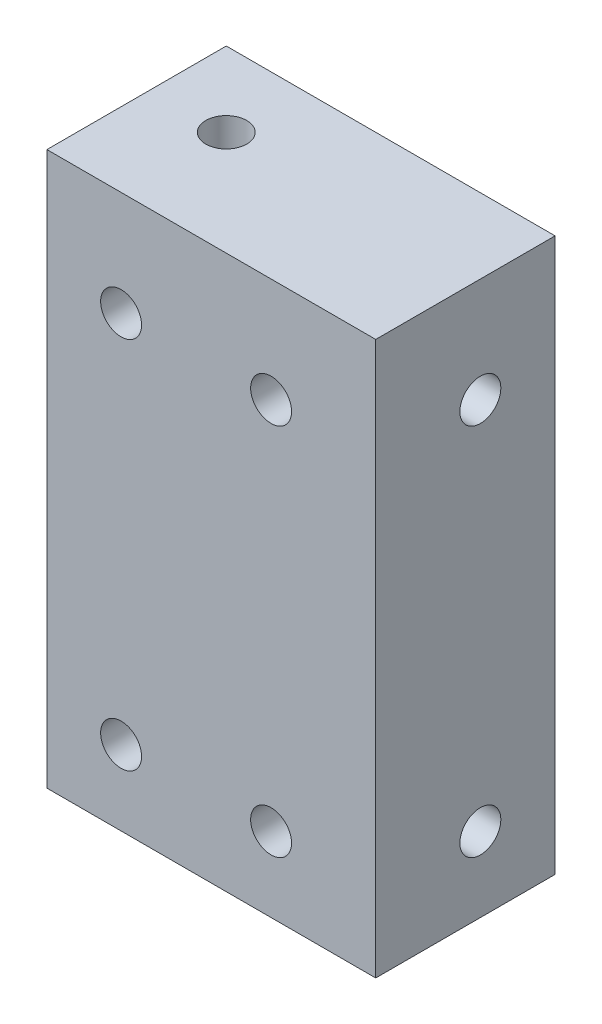
SolidWorks part; units mm, degrees
ref_plane "Front Plane" through (0, 0, 0) normal (0, 0, 1) x (1, 0, 0)
ref_plane "Top Plane" through (0, 0, 0) normal (0, 1, 0) x (1, 0, 0)
ref_plane "Right Plane" through (0, 0, 0) normal (1, 0, 0) x (0, 0, -1)
sketch "Sketch1" plane through (0, 0, 0) normal (0, 0, 1) x (1, 0, 0)
  line L1 (-229.0682, -521.2775) -> (-189.0682, -521.2775)
  line L2 (-229.0682, -521.2775) -> (-229.0682, -451.2775)
  line L3 (-229.0682, -451.2775) -> (-189.0682, -451.2775)
  line L4 (-189.0682, -521.2775) -> (-189.0682, -451.2775)
  line L5 (-229.0682, -521.2775) -> (-189.0682, -451.2775) construction
  line L6 (-229.0682, -451.2775) -> (-189.0682, -521.2775) construction
  circle A0 centre (-199.0682, -461.2775) radius 2.74
  circle A1 centre (-219.1391, -461.2775) radius 2.74
  circle A2 centre (-219.1391, -511.2775) radius 2.74
  circle A3 centre (-199.0682, -511.2775) radius 2.74
  point P0 (-209.0682, -486.2775)
  point P13 (0, 0)
  point P14 (0, 0)
  point P15 (0, 0)
  point P18 (-195.8767, -523.5775)
  dimension "D3" = 5.48
  dimension "D6" = 10
  dimension "D1" = 40
  dimension "D2" = 70
  dimension "D4" = 10
  dimension "D5" = 10
extrude "Boss-Extrude1" add sketch "Sketch1" along normal blind 4
sketch "Sketch2" plane through (0, -451.2775, 0) normal (0, 1, 0) x (1, 0, 0)
  line L1 (-229.0682, -4) -> (-189.0682, -4)
  line L2 (-229.0682, -4) -> (-229.0682, 20)
  line L3 (-229.0682, 20) -> (-189.0682, 20)
  line L4 (-189.0682, -4) -> (-189.0682, 20)
  circle A0 centre (-219.0682, 10) radius 2.74
  dimension "D3" = 5.48
  dimension "D4" = 10
  dimension "D5" = 10
  dimension "D1" = 40
  dimension "D2" = 24
extrude "Boss-Extrude2" add sketch "Sketch2" along normal blind 4
sketch "Sketch3" plane through (-189.0682, 0, 0) normal (1, 0, 0) x (0, 0, -1)
  line L1 (-4, -447.2775) -> (20, -447.2775)
  line L2 (-4, -447.2775) -> (-4, -521.2775)
  line L3 (-4, -521.2775) -> (20, -521.2775)
  line L4 (20, -447.2775) -> (20, -521.2775)
  circle A0 centre (10, -461.2775) radius 2.74
  circle A1 centre (10, -511.2775) radius 2.74
  dimension "D3" = 5.48
  dimension "D4" = 10
  dimension "D6" = 10
  dimension "D1" = 24
  dimension "D2" = 74
  dimension "D5" = 14
extrude "Boss-Extrude3" add sketch "Sketch3" along normal blind 4
